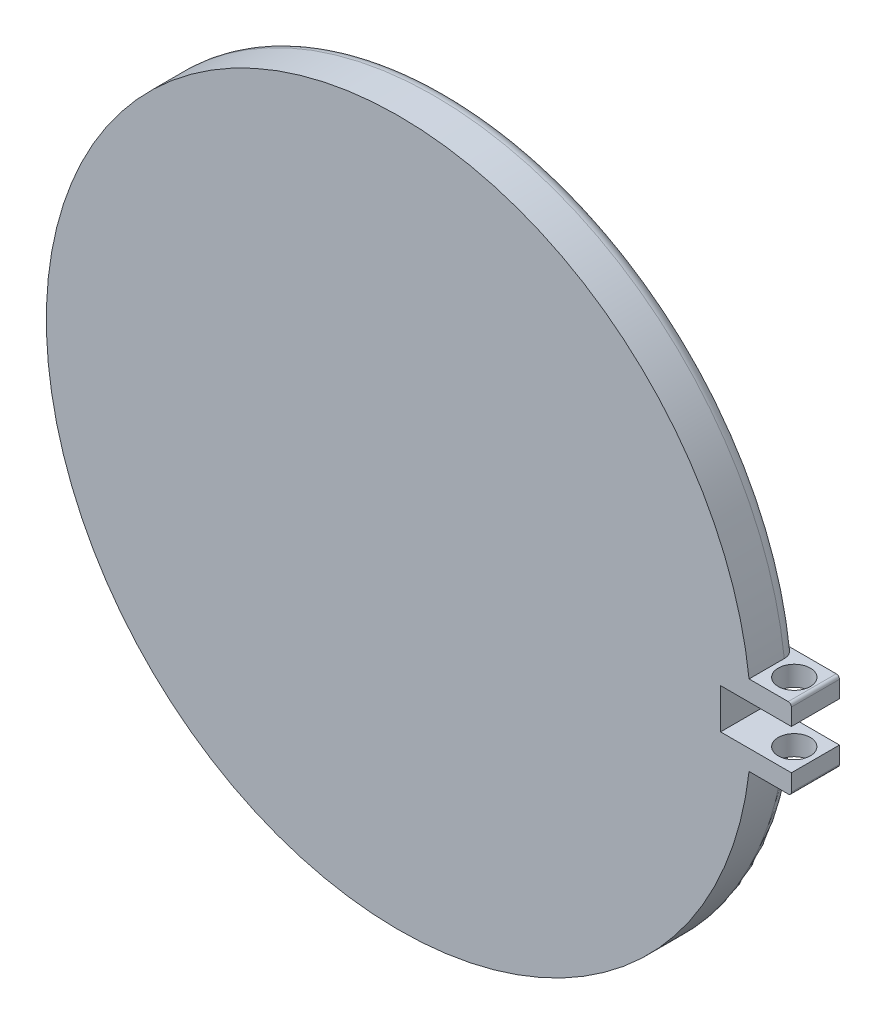
SolidWorks part; units mm, degrees
ref_plane "Front Plane" through (0, 0, 0) normal (0, 0, 1) x (1, 0, 0)
ref_plane "Top Plane" through (0, 0, 0) normal (0, 1, 0) x (1, 0, 0)
ref_plane "Right Plane" through (0, 0, 0) normal (1, 0, 0) x (0, 0, -1)
sketch "Sketch1" plane through (0, 0, 0) normal (0, 0, 1) x (1, 0, 0)
  line L0 (-22, 0) -> (22, 0) construction
  circle A1 centre (0, 0) radius 22
  dimension "D1" = 44
extrude "Boss-Extrude1" add sketch "Sketch1" along normal blind 3
sketch "Sketch2" plane through (0, 0, 3) normal (0, 0, 1) x (1, 0, 0)
  line L1 (19.5, 2.5) -> (24.5, 2.5)
  line L2 (19.5, 2.5) -> (19.5, -2.5)
  line L3 (19.5, -2.5) -> (24.5, -2.5)
  line L4 (24.5, 2.5) -> (24.5, -2.5)
  line L5 (19.5, 2.5) -> (24.5, -2.5) construction
  line L6 (19.5, -2.5) -> (24.5, 2.5) construction
  circle A0 centre (0, 0) radius 22 construction
  point P0 (22, 0)
  dimension "D1" = 5
  dimension "D2" = 5
extrude "Boss-Extrude2" add sketch "Sketch2" against normal blind 3
sketch "Sketch3" plane through (0, 2.5, 0) normal (0, 1, 0) x (1, 0, 0)
  line L0 (21.8575, -1.5) -> (24.5, -1.5) construction
  line L1 (21.8575, -3) -> (21.8575, 0) construction
  line L2 (24.5, 0) -> (24.5, -3) construction
  line L3 (23.1787, 0) -> (23.1787, -3) construction
  line L4 (24.5, 0) -> (21.8575, 0) construction
  line L5 (24.5, -3) -> (21.8575, -3) construction
  circle A0 centre (23.1787, -1.5) radius 1
  dimension "D1" = 2
extrude "Cut-Extrude1" cut sketch "Sketch3" against normal through all both and the other way through all
sketch "Sketch4" plane through (24.5, 0, 0) normal (1, 0, 0) x (0, 0, -1)
  line L0 (-1.5, 2.5) -> (-1.5, -2.5) construction
  line L1 (0, 2.5) -> (-3, 2.5) construction
  line L2 (0, -2.5) -> (-3, -2.5) construction
  line L3 (-3, -2.5) -> (-3, 2.5) construction
  line L4 (0, 1.25) -> (-3, 1.25)
  line L5 (0, 1.25) -> (0, -1.25)
  line L6 (0, -1.25) -> (-3, -1.25)
  line L7 (-3, 1.25) -> (-3, -1.25)
  line L8 (0, 1.25) -> (-3, -1.25) construction
  line L9 (0, -1.25) -> (-3, 1.25) construction
  point P6 (-1.5, 0)
  dimension "D1" = 2.5
extrude "Cut-Extrude2" cut sketch "Sketch4" against normal blind 2.6
fillet "Fillet1" radius 0.2 2 edges at (24.5, -2.5, 1.5) (24.5, 2.5, 1.5)
fillet "Fillet2" radius 0.8 1 edges at (-22, 0, 0)
sketch "Sketch5" plane through (21.9, 0, 0) normal (1, 0, 0) x (0, 0, -1)
  line L0 (-3, -1.25) -> (0, -1.25) construction
  line L1 (-3, 1.25) -> (0, 1.25)
  line L2 (-3, 1.25) -> (-3, -1.25)
  line L3 (-3, -1.25) -> (0, -1.25)
  line L4 (0, 1.25) -> (0, -1.25)
  point P7 (0, -1.25)
extrude "Cut-Extrude3" cut sketch "Sketch5" against normal blind 1.82
